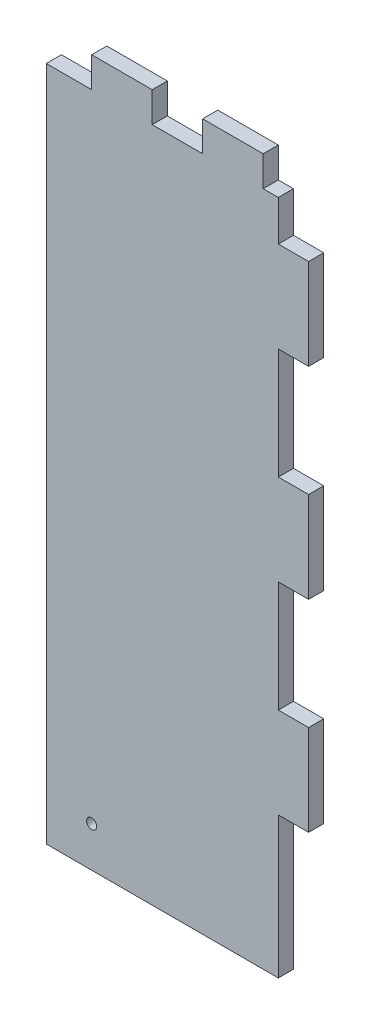
SolidWorks part; units mm, degrees
material "Plywood"
ref_plane "Plan de face" through (0, 0, 0) normal (0, 0, 1) x (1, 0, 0)
ref_plane "Plan de dessus" through (0, 0, 0) normal (0, 1, 0) x (1, 0, 0)
ref_plane "Plan de droite" through (0, 0, 0) normal (1, 0, 0) x (0, 0, -1)
sketch "Esquisse1" plane through (0, 0, 0) normal (0, 0, 1) x (1, 0, 0)
  line L1 (-5.2468, -43.1169) -> (46.7532, -43.1169)
  line L2 (-5.2468, -43.1169) -> (-5.2468, 96.8831)
  line L3 (-5.2468, 96.8831) -> (46.7532, 96.8831)
  line L4 (46.7532, -43.1169) -> (46.7532, 96.8831)
  dimension "D1" = 140
  dimension "D2" = 52
extrude "Boss.-Extru.1" add sketch "Esquisse1" along normal blind 3
sketch "Esquisse2" plane through (0, 0, 3) normal (0, 0, 1) x (1, 0, 0)
  line L0 (46.7532, 96.8831) -> (-5.2468, 96.8831) construction
  line L1 (-5.2468, 96.8831) -> (3.7532, 96.8831)
  line L2 (-5.2468, 96.8831) -> (-5.2468, 90.8831)
  line L3 (-5.2468, 90.8831) -> (3.7532, 90.8831)
  line L4 (3.7532, 96.8831) -> (3.7532, 90.8831)
  line L5 (15.7532, 96.8831) -> (25.7532, 96.8831)
  line L6 (15.7532, 96.8831) -> (15.7532, 90.8831)
  line L7 (15.7532, 90.8831) -> (25.7532, 90.8831)
  line L8 (25.7532, 96.8831) -> (25.7532, 90.8831)
  line L9 (37.7532, 96.8831) -> (37.7532, 90.8831)
  line L10 (37.7532, 90.8831) -> (40.7532, 90.8831)
  line L11 (40.7532, 90.8831) -> (40.7532, 82.8831)
  line L12 (40.7532, 82.8831) -> (46.7532, 82.8831)
  line L13 (46.7532, -43.1169) -> (46.7532, 96.8831) construction
  line L14 (46.7532, 82.8831) -> (46.7532, 96.8831)
  line L15 (46.7532, 96.8831) -> (37.7532, 96.8831)
  line L16 (46.7532, 17.8831) -> (40.7532, 17.8831) construction
  line L17 (46.7532, 42.8831) -> (40.7532, 42.8831)
  line L18 (46.7532, 42.8831) -> (46.7532, 64.8831)
  line L19 (46.7532, 64.8831) -> (40.7532, 64.8831)
  line L20 (40.7532, 42.8831) -> (40.7532, 64.8831)
  line L21 (46.7532, 2.8831) -> (40.7532, 2.8831)
  line L22 (46.7532, 2.8831) -> (46.7532, 24.8831)
  line L23 (46.7532, 24.8831) -> (40.7532, 24.8831)
  line L24 (40.7532, 2.8831) -> (40.7532, 24.8831)
  line L25 (46.7532, -43.1169) -> (40.7532, -43.1169)
  line L26 (46.7532, -43.1169) -> (46.7532, -15.1169)
  line L27 (46.7532, -15.1169) -> (40.7532, -15.1169)
  line L28 (40.7532, -43.1169) -> (40.7532, -15.1169)
  line L29 (46.7532, -22.1169) -> (40.7532, -22.1169) construction
  line L30 (46.7532, 2.8831) -> (40.7532, 2.8831) construction
  line L31 (40.6826, -35.1169) -> (0.6826, -35.1169) construction
  circle A0 centre (3.7532, -35.1169) radius 1
  dimension "D13" = 2
  dimension "D1" = 6
  dimension "D2" = 0
  dimension "D3" = 0
  dimension "D4" = 0
  dimension "D5" = 0
  dimension "D6" = 0
  dimension "D7" = 0
  dimension "D8" = 7
  dimension "D9" = 0
  dimension "D10" = 7
  dimension "D11" = 7
  dimension "D12" = 0
  dimension "D14" = 0
  dimension "D15" = 43
extrude "Enlèv. mat.-Extru.1" cut sketch "Esquisse2" against normal through all
sketch "Esquisse3" plane through (0, 0, 3) normal (0, 0, 1) x (1, 0, 0)
